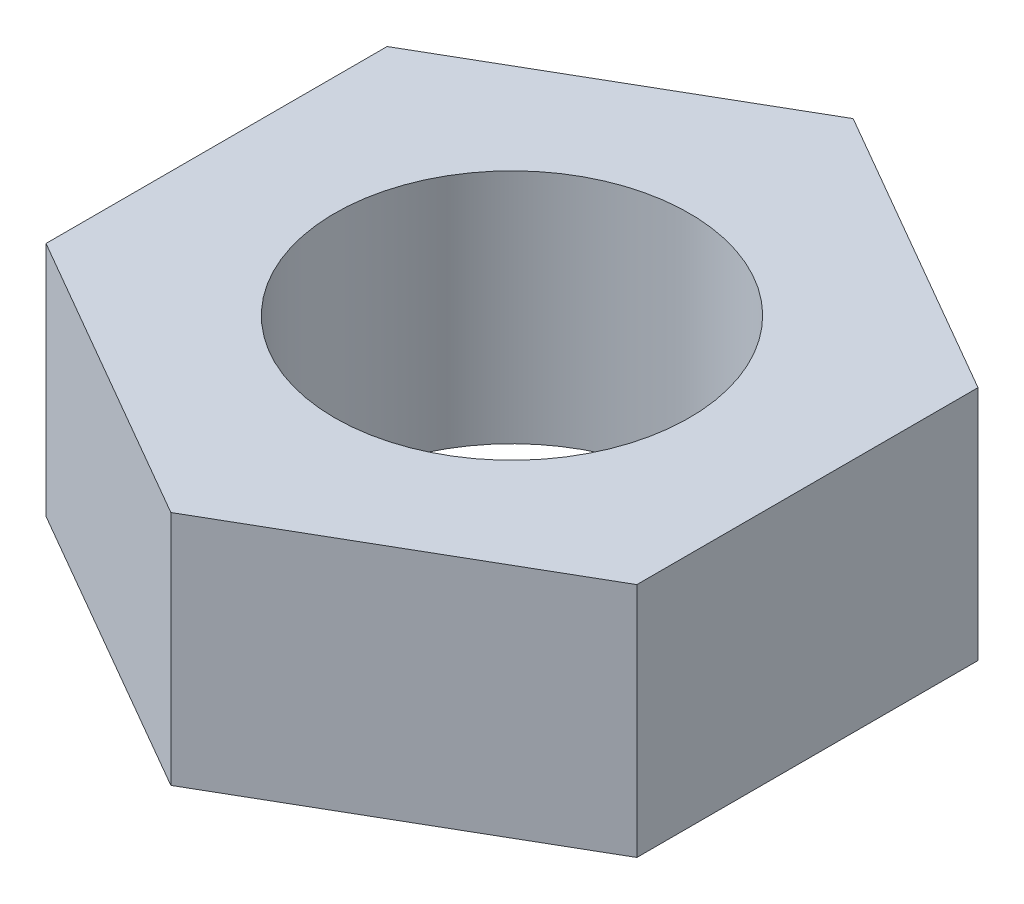
SolidWorks part; units mm, degrees
ref_plane "Front Plane" through (0, 0, 0) normal (0, 0, 1) x (1, 0, 0)
ref_plane "Top Plane" through (0, 0, 0) normal (0, 1, 0) x (1, 0, 0)
ref_plane "Right Plane" through (0, 0, 0) normal (1, 0, 0) x (0, 0, -1)
sketch "Sketch1" plane through (0, 0, 0) normal (0, 1, 0) x (1, 0, 0)
  line L1 (0, 5.7735) -> (-5, 2.8868)
  line L2 (-5, 2.8868) -> (-5, -2.8868)
  line L3 (-5, -2.8868) -> (0, -5.7735)
  line L4 (0, -5.7735) -> (5, -2.8868)
  line L5 (5, -2.8868) -> (5, 2.8868)
  line L6 (5, 2.8868) -> (0, 5.7735)
  circle A0 centre (0, 0) radius 5 construction
  dimension "D1" = 10
extrude "Boss-Extrude1" add sketch "Sketch1" along normal blind 4 contours L5 L6 L1 L2 L3 L4
sketch "Sketch2" plane through (0, 4, 0) normal (0, 1, 0) x (1, 0, 0)
  circle A0 centre (0, 0) radius 3
  dimension "D1" = 6
extrude "Cut-Extrude1" cut sketch "Sketch2" against normal up to next
